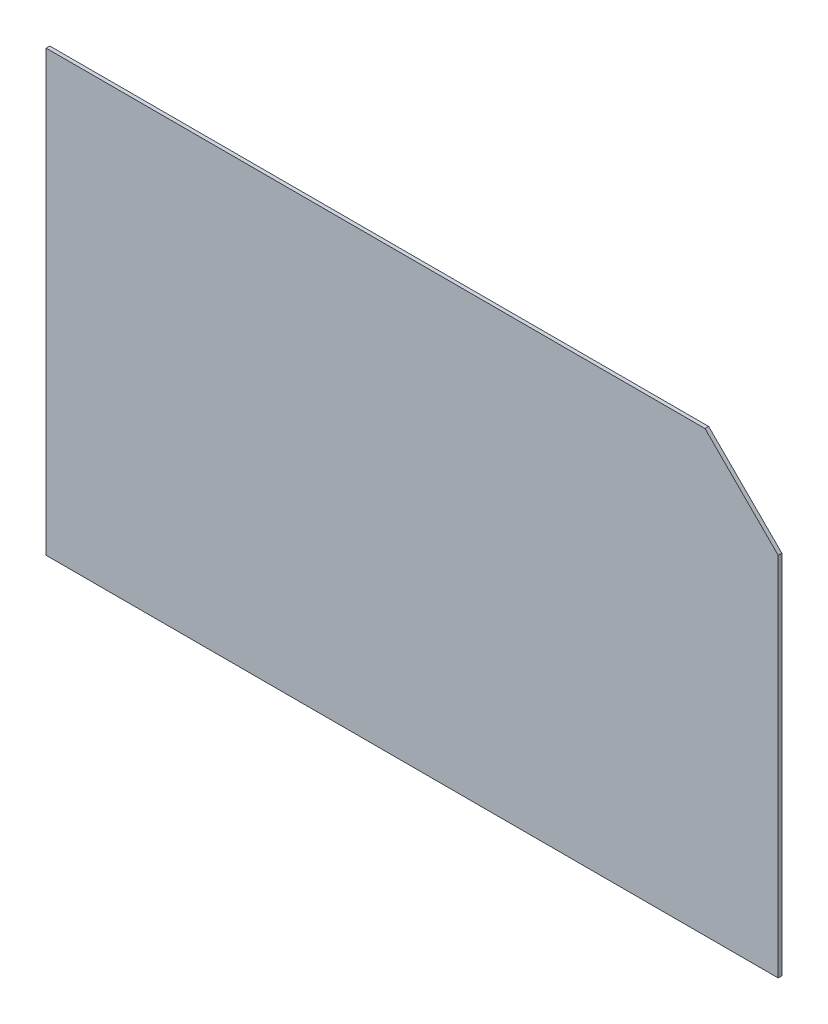
SolidWorks part; units mm, degrees
ref_plane "Front Plane" through (0, 0, 0) normal (0, 0, 1) x (1, 0, 0)
ref_plane "Top Plane" through (0, 0, 0) normal (0, 1, 0) x (1, 0, 0)
ref_plane "Right Plane" through (0, 0, 0) normal (1, 0, 0) x (0, 0, -1)
sketch "Sketch2" plane through (0, 0, 0) normal (0, 0, 1) x (1, 0, 0)
  line L1 (-2105.8965, 2647.4128) -> (2894.1035, 2647.4128)
  line L2 (-2105.8965, 2647.4128) -> (-2105.8965, -352.5872)
  line L3 (-2105.8965, -352.5872) -> (2894.1035, -352.5872)
  line L4 (2894.1035, 2647.4128) -> (2894.1035, -352.5872)
  dimension "wall_length" = 5000
  dimension "wall_height" = 3000
extrude "Boss-Extrude1" add sketch "Sketch2" against normal blind 25
sketch "Sketch3" plane through (0, 0, 0) normal (0, 0, 1) x (1, 0, 0)
  line L5 (2894.1035, 2147.4128) -> (2894.1035, 2647.4128)
  line L6 (2894.1035, -352.5872) -> (2894.1035, 2647.4128) construction
  line L7 (2894.1035, 2647.4128) -> (2394.1035, 2647.4128)
  line L8 (2894.1035, 2647.4128) -> (-2105.8965, 2647.4128) construction
  line L9 (2394.1035, 2647.4128) -> (2894.1035, 2147.4128)
  dimension "D1" = 500
  dimension "D2" = 45
extrude "Cut-Extrude1" cut sketch "Sketch3" against normal blind 932
